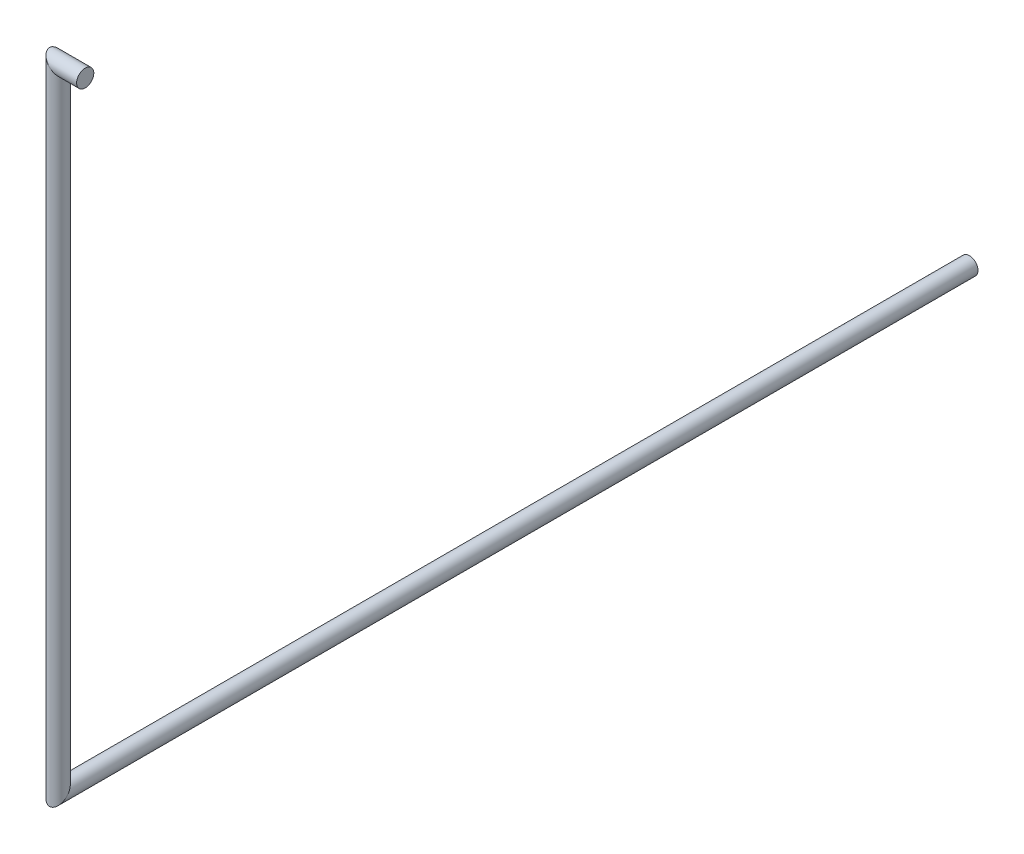
SolidWorks part; units mm, degrees
ref_plane "Alzado" through (0, 0, 0) normal (0, 0, 1) x (1, 0, 0)
ref_plane "Planta" through (0, 0, 0) normal (0, 1, 0) x (1, 0, 0)
ref_plane "Vista lateral" through (0, 0, 0) normal (1, 0, 0) x (0, 0, -1)
sketch "Croquis1" plane through (0, 0, 0) normal (0, 0, 1) x (1, 0, 0)
  circle A0 centre (0, 0) radius 9.525
  dimension "D1" = 19.05
extrude "Saliente-Extruir1" add sketch "Croquis1" along normal blind 10
sketch3d "Croquis3D1"
  line L0 (0, 0, 10) -> (0, 0, 1010)
  line L1 (0, 0, 10) -> (0, 0, 0) construction
  line L2 (0, 0, 1010) -> (0, 700, 1010)
  line L3 (0, 700, 1010) -> (30, 700, 1010)
  dimension "D1" = 1000
  dimension "D2" = 700
  dimension "D3" = 30
sketch "Croquis2" plane through (0, 0, 10) normal (0, 0, 1) x (1, 0, 0)
  circle A0 centre (0, 0) radius 9.525
sweep "Barrer1" add profiles "Croquis2" path "Croquis3D1"
